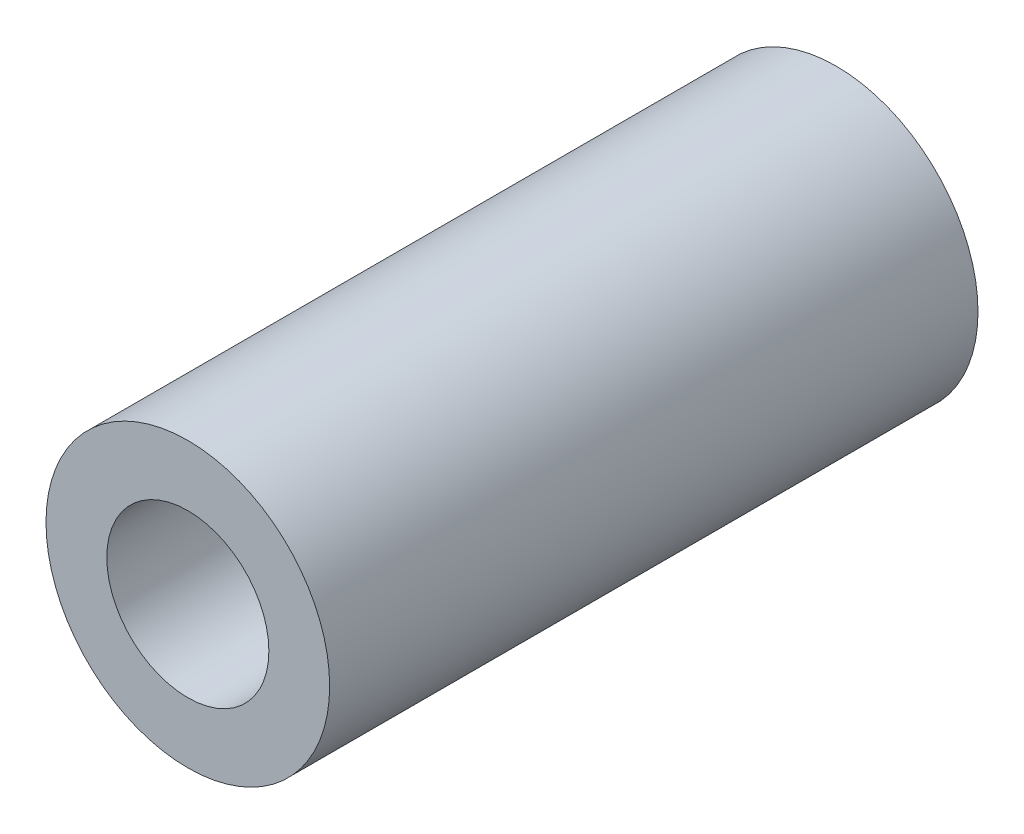
SolidWorks part; units mm, degrees
ref_plane "Front Plane" through (0, 0, 0) normal (0, 0, 1) x (1, 0, 0)
ref_plane "Top Plane" through (0, 0, 0) normal (0, 1, 0) x (1, 0, 0)
ref_plane "Right Plane" through (0, 0, 0) normal (1, 0, 0) x (0, 0, -1)
sketch "Sketch1" plane through (0, 0, 0) normal (1, 0, 0) x (0, 0, -1)
  line L0 (0, 0.7354) -> (1.007, 0.7354) construction
  line L2 (-2, 1.6104) -> (2, 1.6104)
  line L3 (-2, 1.6104) -> (-2, 1.2354)
  line L4 (-2, 1.2354) -> (2, 1.2354)
  line L5 (2, 1.6104) -> (2, 1.2354)
  point P7 (0, 0)
  point P8 (0, 1.2354)
  dimension "D1" = 4
  dimension "D2" = 0.5
  dimension "D3" = 0.875
revolve "Revolve1" add sketch "Sketch1" angle 360 about L0
